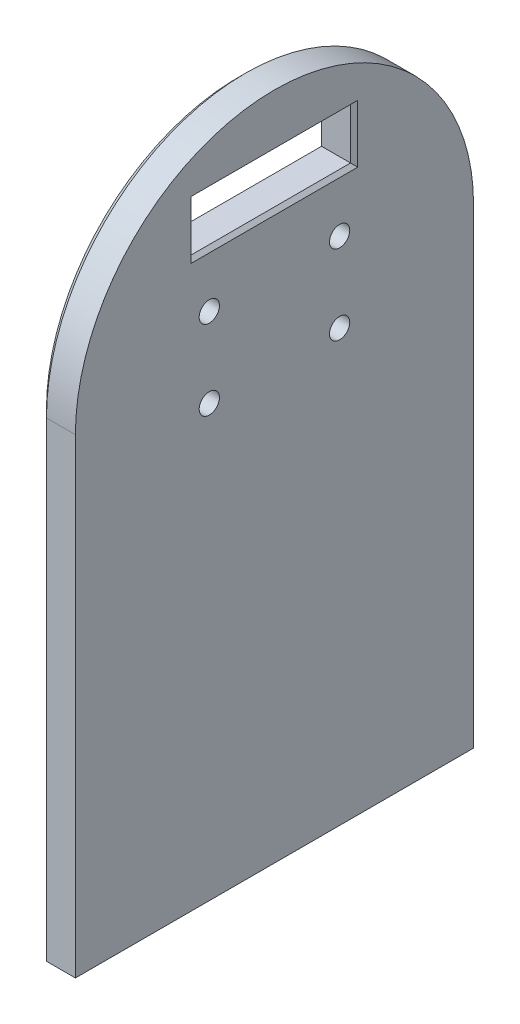
SolidWorks part; units mm, degrees
ref_plane "Front" through (0, 0, 0) normal (0, 0, 1) x (1, 0, 0)
ref_plane "Top" through (0, 0, 0) normal (0, 1, 0) x (1, 0, 0)
ref_plane "Right" through (0, 0, 0) normal (1, 0, 0) x (0, 0, -1)
sketch "草图1" plane through (0, 0, 0) normal (1, 0, 0) x (0, 0, -1)
  line L0 (-27.5, 0) -> (-27.5, -65)
  line L1 (-27.5, -65) -> (27.5, -65)
  line L2 (27.5, -65) -> (27.5, 0)
  arc A0 (27.5, 0) -> (-27.5, 0) centre (0, 0) ccw
  circle A1 centre (0, 0) radius 22 construction
extrude "凸台-拉伸1" add sketch "草图1" along normal blind 5
sketch "草图2" plane through (5, 0, 0) normal (1, 0, 0) x (0, 0, -1)
  line L1 (-9, -5.5) -> (9, -5.5) construction
  line L2 (-9, -5.5) -> (-9, 5.5) construction
  line L3 (-9, 5.5) -> (9, 5.5) construction
  line L4 (9, -5.5) -> (9, 5.5) construction
  line L5 (-9, -5.5) -> (9, 5.5) construction
  line L6 (-9, 5.5) -> (9, -5.5) construction
  circle A0 centre (-9, 5.5) radius 1.4
  circle A1 centre (9, 5.5) radius 1.4
  circle A2 centre (9, -5.5) radius 1.4
  circle A3 centre (-9, -5.5) radius 1.4
  arc A4 (27.5, 0) -> (-27.5, 0) centre (0, 0) ccw construction
  point P0 (0, 0)
extrude "切除-拉伸1" cut sketch "草图2" against normal blind 5
chamfer "倒角1" distance 1 angle 45 4 edges at (0, -32.5, -27.5) (0, -32.5, 27.5) (0, 27.5, 0) (0, -65, 0)
sketch "草图4" plane through (0, 0, 0) normal (-1, 0, 0) x (0, 0, 1)
  line L1 (-11, 20) -> (11, 20)
  line L2 (-11, 20) -> (-11, 13)
  line L3 (-11, 13) -> (11, 13)
  line L4 (11, 20) -> (11, 13)
  line L5 (0, 13) -> (0, 20) construction
  line L6 (-11, 16.5) -> (11, 16.5) construction
  circle A0 centre (9, 5.5) radius 1.4 construction
  point P100 (0, 16.5)
  dimension "D1" = 22
  dimension "D2" = 7
  dimension "D3" = 0
  dimension "D4" = 11
extrude "切除-拉伸4" cut sketch "草图4" against normal blind 10
chamfer "倒角2" distance 0.5 angle 45 8 edges at (0, 16.5, 11) (0, 20, 0) (0, 16.5, -11) (0, 13, 0) (5, 16.5, 11) (5, 20, 0) (5, 16.5, -11) (5, 13, 0)
